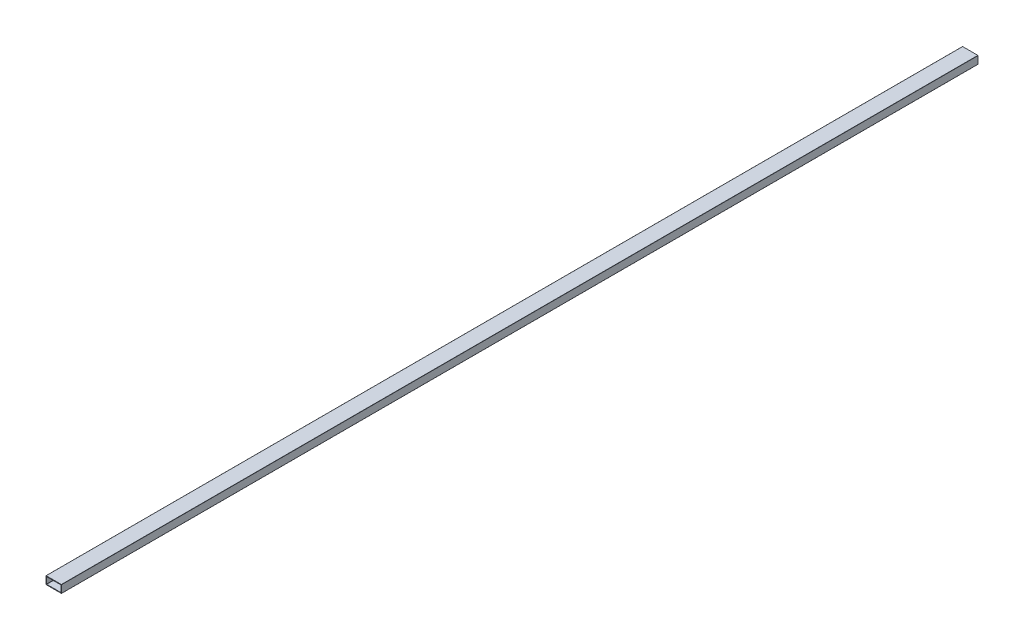
SolidWorks part; units mm, degrees
material "AISI 1035 Acero (SS)"
ref_plane "Alzado" through (0, 0, 0) normal (0, 0, 1) x (1, 0, 0)
ref_plane "Planta" through (0, 0, 0) normal (0, 1, 0) x (1, 0, 0)
ref_plane "Vista lateral" through (0, 0, 0) normal (1, 0, 0) x (0, 0, -1)
sketch "Croquis1" plane through (0, 0, 0) normal (0, 0, 1) x (1, 0, 0)
  line L0 (-47, -21.6) -> (-47, 21.6)
  line L1 (-50.8, -25.4) -> (50.8, -25.4)
  line L2 (-50.8, -25.4) -> (-50.8, 25.4)
  line L3 (-50.8, 25.4) -> (50.8, 25.4)
  line L4 (50.8, -25.4) -> (50.8, 25.4)
  line L5 (-50.8, -25.4) -> (50.8, 25.4) construction
  line L6 (-50.8, 25.4) -> (50.8, -25.4) construction
  line L7 (-47, 21.6) -> (47, 21.6)
  line L8 (47, -21.6) -> (47, 21.6)
  line L9 (-47, -21.6) -> (47, -21.6)
  point P0 (0, 0)
  dimension "D1" = 50.8
  dimension "D2" = 101.6
  dimension "D3" = 3.8
extrude "Saliente-Extruir1" add sketch "Croquis1" against normal blind 6000
fillet "Redondeo1" radius 1 8 edges at (-47, 21.6, -3000) (47, 21.6, -3000) (47, -21.6, -3000) (-50.8, -25.4, -3000) (-50.8, 25.4, -3000) (-47, -21.6, -3000) (50.8, -25.4, -3000) (50.8, 25.4, -3000)
